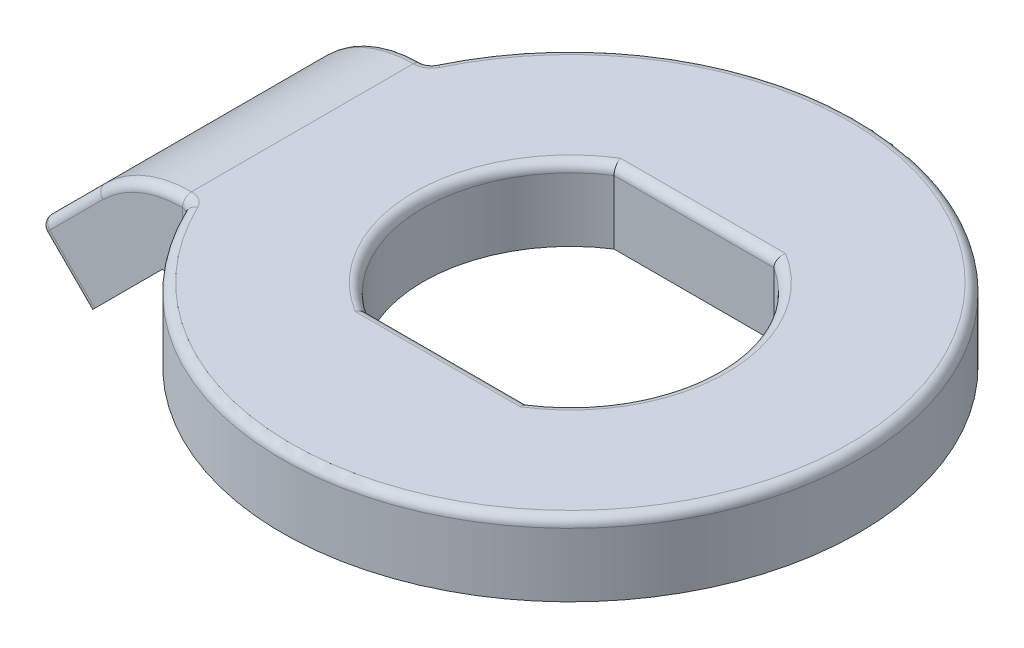
SolidWorks part; units mm, degrees
material "Plain Carbon Steel"
ref_plane "Front Plane" through (0, 0, 0) normal (0, 0, 1) x (1, 0, 0)
ref_plane "Top Plane" through (0, 0, 0) normal (0, 1, 0) x (1, 0, 0)
ref_plane "Right Plane" through (0, 0, 0) normal (1, 0, 0) x (0, 0, -1)
sketch "Sketch1" plane through (0, 0, 0) normal (0, 1, 0) x (1, 0, 0)
  line L0 (-3.3345, 5.1562) -> (3.3345, 5.1562)
  line L1 (3.3345, -5.1562) -> (-3.3345, -5.1562)
  line L2 (0, 0) -> (-13593.354, 0) construction
  circle A0 centre (0, 0) radius 12.0269
  arc A1 (-3.3345, 5.1562) -> (-3.3345, -5.1562) centre (0, 0) ccw
  arc A2 (3.3345, 5.1562) -> (-3.3345, 5.1562) centre (0, 0) ccw construction
  arc A3 (-3.3345, -5.1562) -> (3.3345, -5.1562) centre (0, 0) ccw construction
  arc A4 (3.3345, -5.1562) -> (3.3345, 5.1562) centre (0, 0) ccw
  dimension "D2" = 12.2809
  dimension "D3" = 24.0538
  dimension "D1" = 10.3124
extrude "Boss-Extrude1" add sketch "Sketch1" along normal blind 3.0378
sketch "Sketch3" plane through (0, 0, 0) normal (0, 0, 1) x (1, 0, 0)
  line L0 (-6.1404, 3.0378) -> (-13.2852, 3.0378)
  line L1 (12.0269, 3.0378) -> (-12.0269, 3.0378) construction
  line L2 (-13.2852, 3.0378) -> (-17.2552, -0.9322)
  line L3 (-17.2552, -0.9322) -> (-15.1071, -3.0802)
  line L4 (-15.1071, -3.0802) -> (-12.0269, 0)
  line L5 (-12.0269, 0) -> (-6.1404, 0)
  line L6 (-12.0269, 3.0378) -> (-12.0269, 0) construction
  line L7 (-6.1404, 3.0378) -> (-6.1404, 0)
  point P11 (0, 0)
  point P12 (-12.0269, 0)
  dimension "D1" = 4.3561
  dimension "D2" = 45
extrude "Boss-Extrude2" add sketch "Sketch3" along normal mid plane 10.0076
fillet "Fillet1" radius 5.08 1 edges at (-13.2852, 3.0378, 0)
fillet "Fillet2" radius 0.381 16 edges at (-16.0142, 0.3089, 5.0038) (-13.125, 2.6511, 5.0038) (-16.0142, 0.3089, -5.0038) (-13.125, 2.6511, -5.0038) (12.0269, 3.0378, 0) (-11.0588, 3.0378, 5.0038) (-11.0588, 3.0378, -5.0038) (6.1404, 3.0378, 0) (0, 3.0378, -5.1562) (-6.1404, 3.0378, 0) (0, 3.0378, 5.1562) (-10.9366, 1.5189, 5.0038) (-10.9366, 1.5189, -5.0038) (-17.2552, -0.9322, 0) (-16.1812, -2.0062, 5.0038) (-16.1812, -2.0062, -5.0038)
